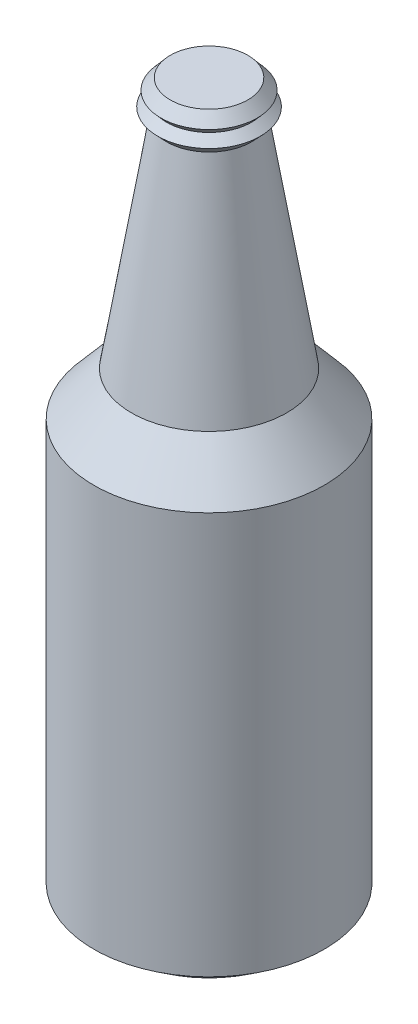
SolidWorks part; units mm, degrees
ref_plane "Front Plane" through (0, 0, 0) normal (0, 0, 1) x (1, 0, 0)
ref_plane "Top Plane" through (0, 0, 0) normal (0, 1, 0) x (1, 0, 0)
ref_plane "Right Plane" through (0, 0, 0) normal (1, 0, 0) x (0, 0, -1)
sketch "Sketch1" plane through (0, 0, 0) normal (0, 0, 1) x (1, 0, 0)
  line L0 (-2.1579, 95.6271) -> (2.2658, 95.6271)
  line L1 (2.2658, 95.6271) -> (3.339, 94.3744)
  line L2 (3.339, 94.3744) -> (2.6792, 93.6176)
  line L3 (2.6792, 93.6176) -> (3.6848, 92.741)
  line L4 (3.6848, 92.741) -> (2.6792, 91.6825)
  line L5 (2.6792, 91.6825) -> (6.701, 66.8969)
  line L6 (6.701, 66.8969) -> (10.9935, 61.8866)
  line L7 (10.9935, 61.8866) -> (10.9935, 16.0062)
  line L8 (10.9935, 16.0062) -> (7.768, 13.6159)
  line L9 (-2.1579, 14.6354) -> (-2.1579, 95.6271)
  line L10 (7.768, 13.6159) -> (-2.1579, 13.6159)
  line L11 (-2.1579, 13.6159) -> (-2.1579, 14.6354)
revolve "Revolve1" add sketch "Sketch1" angle 360 about L9
sketch "Sketch2" plane through (0, 0, 0) normal (1, 0, 0) x (0, 0, -1)
